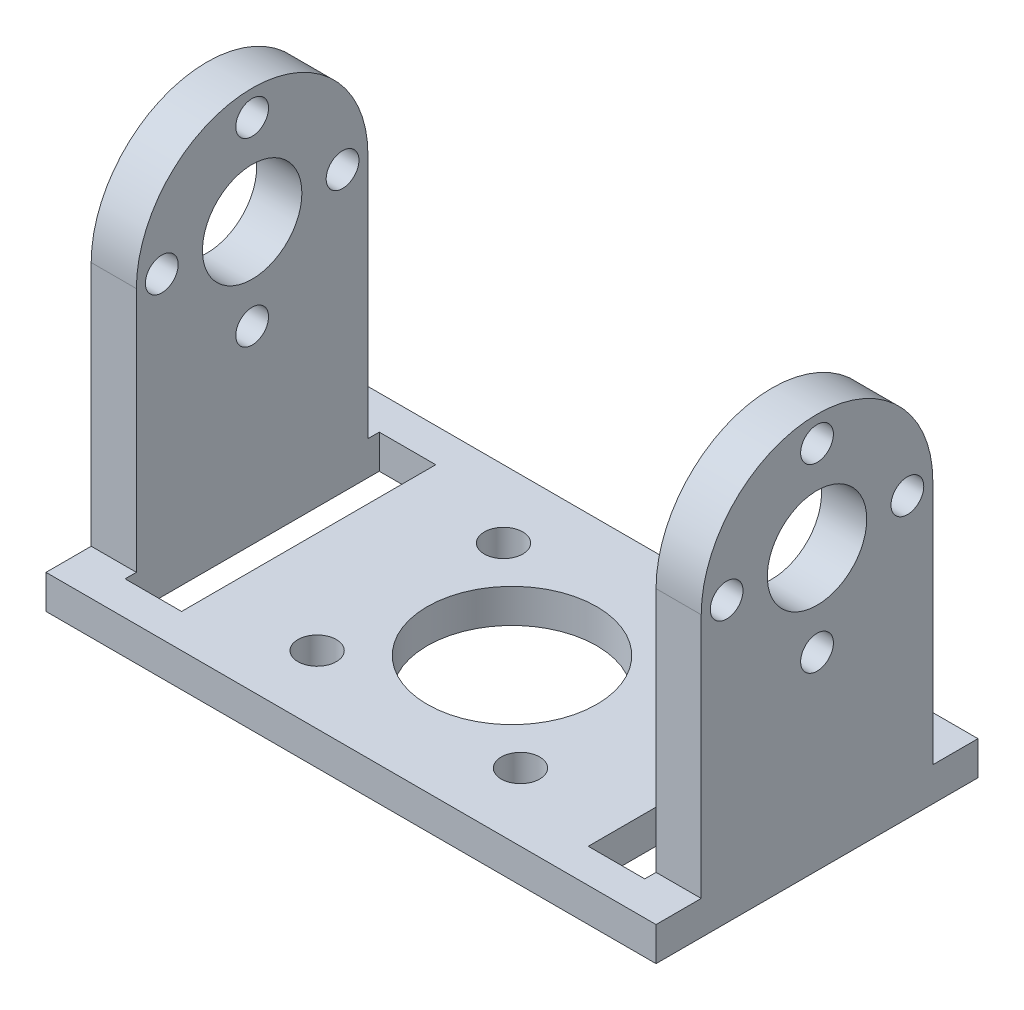
SolidWorks part; units mm, degrees
ref_plane "Front Plane" through (0, 0, 0) normal (0, 0, 1) x (1, 0, 0)
ref_plane "Top Plane" through (0, 0, 0) normal (0, 1, 0) x (1, 0, 0)
ref_plane "Right Plane" through (0, 0, 0) normal (1, 0, 0) x (0, 0, -1)
sketch "Sketch1" plane through (0, 0, 0) normal (0, 1, 0) x (1, 0, 0)
  line L0 (0, 0) -> (0, -7.6155) construction
  line L1 (-18, 14.25) -> (18, 14.25)
  line L2 (-18, 14.25) -> (-18, -14.25)
  line L3 (-18, -14.25) -> (18, -14.25)
  line L4 (18, 14.25) -> (18, -14.25)
  line L5 (0, 0) -> (0, 12.9892) construction
  line L6 (-18, 14.25) -> (-27, 14.25)
  line L7 (-18, 14.25) -> (-18, -14.25)
  line L8 (-18, -14.25) -> (-27, -14.25)
  line L9 (-27, 14.25) -> (-27, -14.25)
  line L10 (18, 14.25) -> (27, 14.25)
  line L11 (18, 14.25) -> (18, -14.25)
  line L12 (18, -14.25) -> (27, -14.25)
  line L13 (27, 14.25) -> (27, -14.25)
  line L14 (-23, 11.25) -> (-18, 11.25)
  line L15 (-23, 11.25) -> (-23, -11.25)
  line L16 (-23, -11.25) -> (-18, -11.25)
  line L17 (-18, 11.25) -> (-18, -11.25)
  line L18 (18, 11.25) -> (18, -11.25)
  line L19 (23, -11.25) -> (18, -11.25)
  line L20 (23, 11.25) -> (23, -11.25)
  line L21 (23, 11.25) -> (18, 11.25)
  circle A0 centre (0, 0) radius 7.5
  circle A1 centre (-9, 8.25) radius 1.7
  circle A2 centre (-9, -8.25) radius 1.7
  circle A3 centre (9, -8.25) radius 1.7
  circle A4 centre (9, 8.25) radius 1.7
  point P0 (0, 0)
  dimension "D3" = 9
  dimension "D4" = 8.25
  dimension "D5" = 8.25
  dimension "D6" = 9
  dimension "D7" = 9
  dimension "D9" = 15
  dimension "D1" = 36
  dimension "D2" = 28.5
  dimension "D8" = 9
  dimension "D10" = 4
  dimension "D11" = 3
  dimension "D12" = 3
  dimension "D13" = 5
extrude "Boss-Extrude2" add sketch "Sketch1" along normal blind 3
sketch "Sketch2" plane through (0, 3, 0) normal (0, 1, 0) x (1, 0, 0)
  line L5 (27, 14.25) -> (27, -14.25) construction
  line L6 (27, 10.25) -> (23, 10.25)
  line L7 (27, 10.25) -> (27, -10.25)
  line L8 (27, -10.25) -> (23, -10.25)
  line L9 (23, 10.25) -> (23, -10.25)
  line L10 (27, 14.25) -> (-27, 14.25) construction
  dimension "D1" = 4
  dimension "D2" = 20.5
  dimension "D3" = 4
extrude "Boss-Extrude3" add sketch "Sketch2" along normal blind 21.75
sketch "Sketch4" plane through (27, 0, 0) normal (1, 0, 0) x (0, 0, -1)
  line L0 (-10.25, 24.75) -> (10.25, 24.75) construction
  circle A0 centre (0, 24.75) radius 10.25
  point P18 (0, 17.75)
extrude "Boss-Extrude4" add sketch "Sketch4" against normal blind 4
ref_plane "Plane1" through (0, 0, 0) normal (1, 0, 0) x (0, 0, -1)
mirror "Mirror1" about plane through (0, 0, 0) normal (1, 0, 0) of "Boss-Extrude3", "Boss-Extrude4"
sketch "Sketch6" plane through (27, 0, 0) normal (1, 0, 0) x (0, 0, -1)
  line L0 (-10.25, 24.75) -> (10.25, 24.75) construction
  line L1 (0, 35) -> (0, 14.5) construction
  circle A6 centre (0, 24.75) radius 4.4
  circle A7 centre (0, 24.75) radius 8
  circle A8 centre (0, 32.75) radius 1.45
  circle A9 centre (8, 24.75) radius 1.45
  circle A10 centre (0, 16.75) radius 1.45
  circle A11 centre (-8, 24.75) radius 1.45
  circle A12 centre (0, 24.75) radius 10.25
  point P21 (0, 24.75)
  dimension "D1" = 8.8
  dimension "D2" = 16
  dimension "D3" = 4
  dimension "D4" = 2.9
extrude "Cut-Extrude3" cut sketch "Sketch6" against normal blind 4 contours A6 | A7 A11 | A7 A11 | A7 A10 | A7 A10 | A7 A9 | A7 A9 | A7 A8 | A7 A8
mirror "Mirror3" about plane through (0, 0, 0) normal (1, 0, 0) of "Cut-Extrude3"
